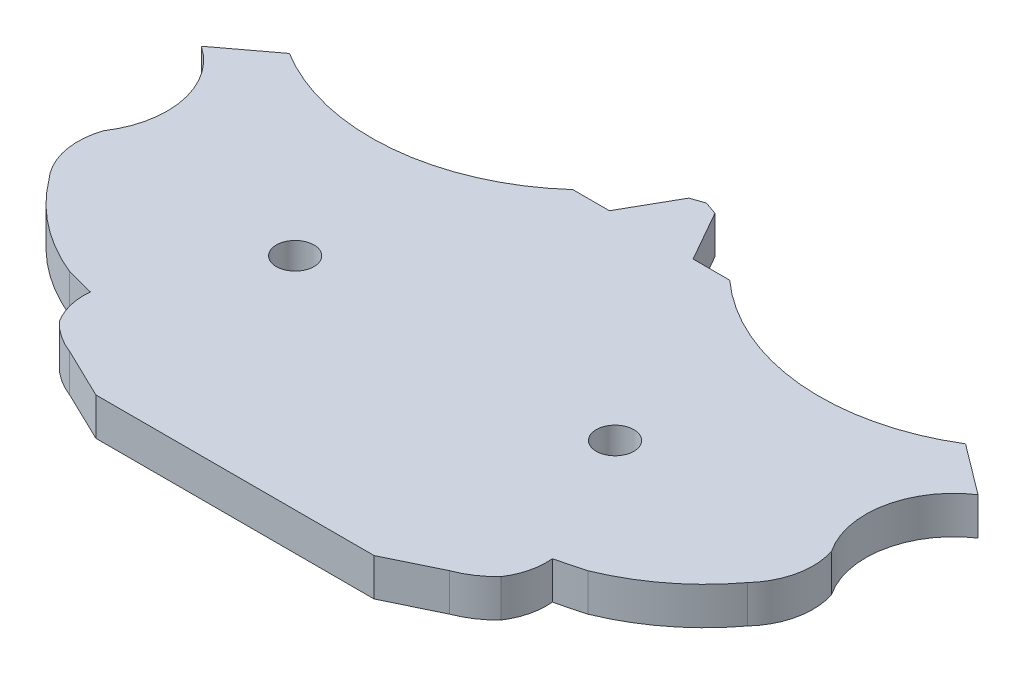
SolidWorks part; units mm, degrees
ref_plane "Front Plane" through (0, 0, 0) normal (0, 0, 1) x (1, 0, 0)
ref_plane "Top Plane" through (0, 0, 0) normal (0, 1, 0) x (1, 0, 0)
ref_plane "Right Plane" through (0, 0, 0) normal (1, 0, 0) x (0, 0, -1)
sketch "Sketch3" plane through (0, 0, 0) normal (0, 1, 0) x (1, 0, 0)
  line L0 (84.4541, 599.5572) -> (574.4541, 599.5572) construction
sketch "Sketch2" plane through (0, 0, 0) normal (0, 1, 0) x (1, 0, 0)
  line L0 (0, 0) -> (0, 57.603) construction
  line L1 (-18.1438, -7.9279) -> (18.1438, -7.9279) construction
  line L2 (-18.1438, -7.9279) -> (-18.1438, 7.9279) construction
  line L3 (-18.1438, 7.9279) -> (18.1438, 7.9279) construction
  line L4 (18.1438, -7.9279) -> (18.1438, 7.9279) construction
  line L5 (-18.1438, -7.9279) -> (18.1438, 7.9279) construction
  line L6 (-18.1438, 7.9279) -> (18.1438, -7.9279) construction
  line L7 (-21.8576, -11.143) -> (21.8576, -11.143) construction
  line L8 (-21.8576, -11.143) -> (-21.8576, 11.143) construction
  line L9 (-21.8576, 11.143) -> (21.8576, 11.143) construction
  line L10 (21.8576, -11.143) -> (21.8576, 11.143) construction
  line L11 (-21.8576, -11.143) -> (21.8576, 11.143) construction
  line L12 (-21.8576, 11.143) -> (21.8576, -11.143) construction
  line L13 (-8.5, 0) -> (8.5, 0) construction
  line L14 (0, 0) -> (0, -8.8619) construction
  line L15 (-20.6395, 7.1502) -> (-17.9674, 9.1598)
  line L16 (-4.1695, 10.4244) -> (4.1695, 10.4244)
  line L17 (-1.5343, -5.6375) -> (1.5343, -5.6375)
  line L18 (-10.0901, -10.3942) -> (-7.3916, -11.6987)
  line L19 (20.6395, 7.1502) -> (17.9674, 9.1598)
  line L20 (-2.2241, 10.4244) -> (-0.6961, 13.1148)
  line L21 (-0.6961, 13.1148) -> (0, 13.358)
  line L22 (2.2241, 10.4244) -> (0.6961, 13.1148)
  line L23 (0.6961, 13.1148) -> (0, 13.358)
  line L24 (-7.3916, -11.6987) -> (-0.7757, -11.143)
  line L25 (-0.7757, -11.143) -> (0, -10.9595)
  line L26 (0.7757, -11.143) -> (0, -10.9595)
  line L27 (7.3916, -11.6987) -> (0.7757, -11.143)
  line L28 (10.0901, -10.3942) -> (7.3916, -11.6987)
  line L29 (-16.4215, -5.191) -> (-11.7373, -9.2961)
  line L30 (16.4215, -5.191) -> (11.7373, -9.2961)
  line L31 (-7.3916, -11.6987) -> (7.3916, -11.6987)
  line L33 (-32.5, -20.0045) -> (32.5, -20.0045)
  line L34 (-32.5, -20.0045) -> (-32.5, 20.0045)
  line L35 (-32.5, 20.0045) -> (32.5, 20.0045)
  line L36 (32.5, -20.0045) -> (32.5, 20.0045)
  line L37 (-32.5, -20.0045) -> (32.5, 20.0045) construction
  line L38 (-32.5, 20.0045) -> (32.5, -20.0045) construction
  arc A0 (-4.1695, 10.4244) -> (-17.9674, 9.1598) centre (-11.9148, 19.0269) cw
  arc A1 (-20.6395, 7.1502) -> (-19.3461, 0.6629) centre (-23.2364, 3.2599) cw
  arc A2 (-19.3461, 0.6629) -> (-18.559, -3.0217) centre (-15.82, -0.5102) ccw
  arc A3 (-18.559, -3.0217) -> (-13.7831, -6.7121) centre (-9.4985, 3.7682) ccw
  arc A4 (-13.7831, -6.7121) -> (-6.6237, -7.9279) centre (-4.6259, 25.5245) ccw
  arc A5 (-1.5343, -5.6375) -> (-6.6237, -7.9279) centre (-1.5343, -12.4372) ccw
  circle A6 centre (-8.5, 0) radius 1
  arc A7 (13.7831, -6.7121) -> (6.6237, -7.9279) centre (4.6259, 25.5245) cw
  arc A8 (18.559, -3.0217) -> (13.7831, -6.7121) centre (9.4985, 3.7682) cw
  arc A9 (19.3461, 0.6629) -> (18.559, -3.0217) centre (15.82, -0.5102) cw
  arc A10 (20.6395, 7.1502) -> (19.3461, 0.6629) centre (23.2364, 3.2599) ccw
  arc A11 (4.1695, 10.4244) -> (17.9674, 9.1598) centre (11.9148, 19.0269) ccw
  arc A12 (1.5343, -5.6375) -> (6.6237, -7.9279) centre (1.5343, -12.4372) cw
  circle A13 centre (8.5, 0) radius 1
  arc A14 (-12.2767, -7.1024) -> (-11.7373, -9.2961) centre (-8.8887, -7.4325) ccw
  arc A15 (-11.7373, -9.2961) -> (-10.0901, -10.3942) centre (-8.5052, -6.2323) ccw
  arc A16 (12.2767, -7.1024) -> (11.7373, -9.2961) centre (8.8887, -7.4325) cw
  arc A17 (11.7373, -9.2961) -> (10.0901, -10.3942) centre (8.5052, -6.2323) cw
  point P0 (0, 0)
  point P6 (0, 0)
  point P34 (0, 0)
  point P45 (0, 10.4244)
  point P54 (0, -5.6375)
  point P57 (-0.2087, -5.6375)
  point P72 (0, -11.6987)
  dimension "D2" = 65
  dimension "D1" = 17
extrude "Boss-Extrude1" add sketch "Sketch2" along normal blind 2 contours L17 A12 A7 A8 A9 A10 L19 A11 L16 A0 L15 A1 A2 A3 A4 A5 A6 A13 | L22 L23 L21 L20 L16 | A17 A16 A7 A12 L17 A5 A4 A14 A15 L18 L24 L25 L26 L27 L28 | L24 L31 L27 L26 L25
sketch "Sketch4" plane through (0, 0, 0) normal (0, 1, 0) x (1, 0, 0)
  line L0 (0, 0) -> (0, -15.9627) construction
  line L1 (0, 0) -> (0, 46.0631) construction
scale "Scale1" bodies to scale 101 scale about centroid uniform scaling yes scale factor 2
